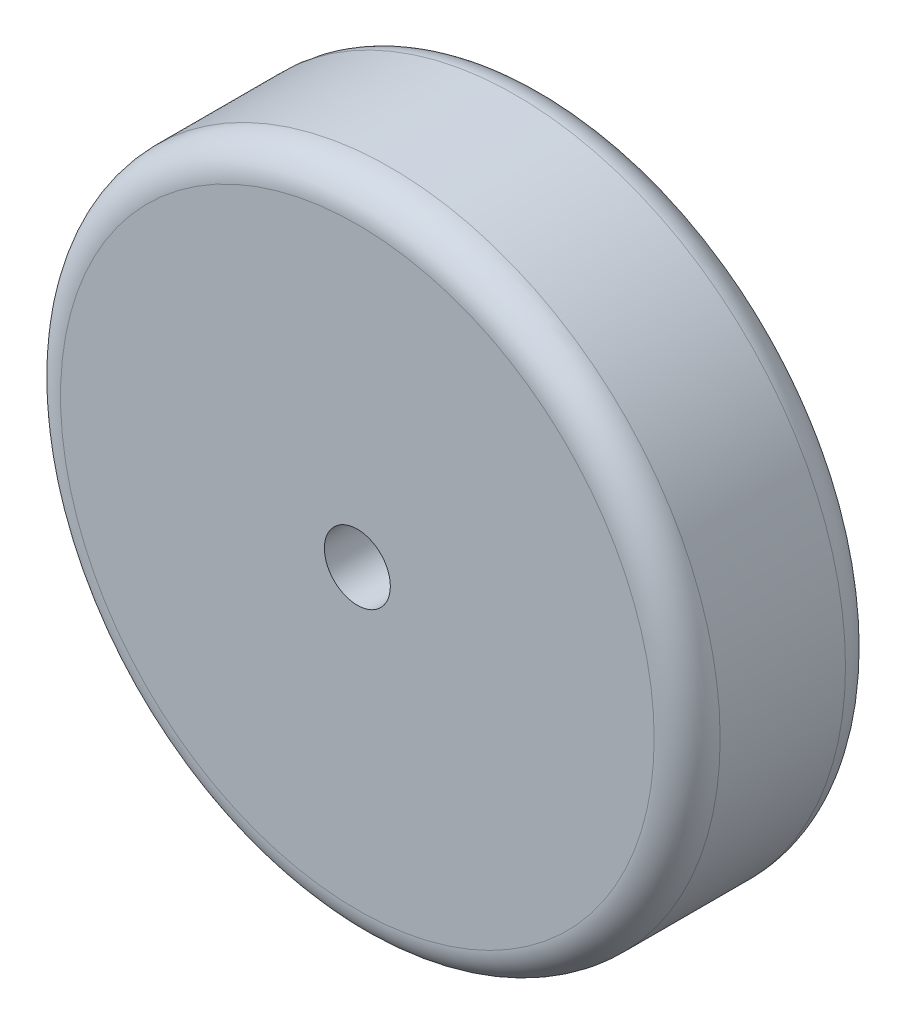
SolidWorks part; units mm, degrees
material "硅橡胶"
ref_plane "前视基准面" through (0, 0, 0) normal (0, 0, 1) x (1, 0, 0)
ref_plane "上视基准面" through (0, 0, 0) normal (0, 1, 0) x (1, 0, 0)
ref_plane "右视基准面" through (0, 0, 0) normal (1, 0, 0) x (0, 0, -1)
other "Configuration Table"
sketch "草图1" plane through (0, 0, 0) normal (0, 0, 1) x (1, 0, 0)
  circle A0 centre (0, 0) radius 50
  dimension "D1" = 100
extrude "凸台-拉伸1" add sketch "草图1" along normal blind 29
sketch "草图2" plane through (0, 0, 29) normal (0, 0, 1) x (1, 0, 0)
  circle A0 centre (0, 0) radius 5
  dimension "D1" = 10
extrude "切除-拉伸1" cut sketch "草图2" against normal through all
fillet "圆角1" radius 5 2 edges at (50, 0, 0) (50, 0, 29)
